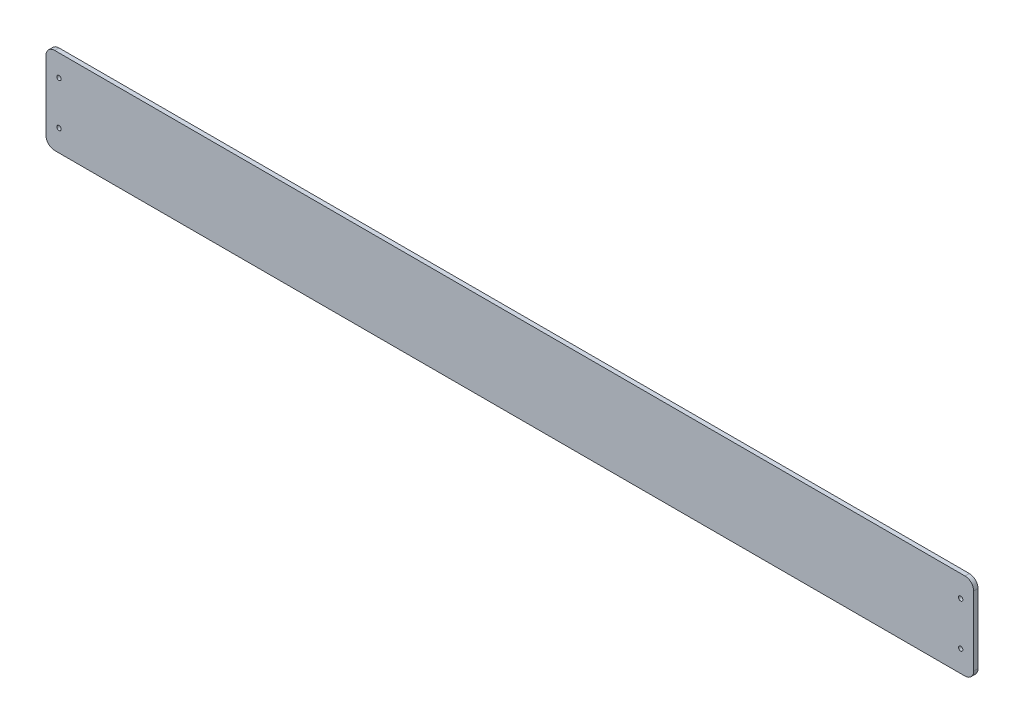
SolidWorks part; units mm, degrees
ref_plane "Alzado" through (0, 0, 0) normal (0, 0, 1) x (1, 0, 0)
ref_plane "Planta" through (0, 0, 0) normal (0, 1, 0) x (1, 0, 0)
ref_plane "Vista lateral" through (0, 0, 0) normal (1, 0, 0) x (0, 0, -1)
sketch "Croquis1" plane through (0, 0, 0) normal (0, 0, 1) x (1, 0, 0)
  line L1 (535, -50) -> (-535, -50)
  line L2 (535, -50) -> (535, 50)
  line L3 (535, 50) -> (-535, 50)
  line L4 (-535, -50) -> (-535, 50)
  line L5 (535, -50) -> (-535, 50) construction
  line L6 (535, 50) -> (-535, -50) construction
  point P0 (0, 0)
  dimension "D1" = 1070
  dimension "D2" = 100
extrude "Extruir1" add sketch "Croquis1" along normal blind 5
fillet "Redondeo1" radius 10 4 edges at (535, -50, 2.5) (535, 50, 2.5) (-535, -50, 2.5) (-535, 50, 2.5)
sketch "Croquis2" plane through (0, 0, 5) normal (0, 0, 1) x (1, 0, 0)
  line L0 (-520, 50) -> (-520, -50) construction
  line L1 (525, 50) -> (-525, 50) construction
  line L2 (-525, -50) -> (525, -50) construction
  line L3 (-535, 40) -> (-535, -40) construction
  line L4 (0, 0) -> (0, 50) construction
  line L5 (0, 0) -> (535, 0) construction
  line L6 (535, -40) -> (535, 40) construction
  circle A0 centre (-520, 25) radius 2.5
  circle A1 centre (-520, -25) radius 2.5
  circle A2 centre (520, -25) radius 2.5
  circle A3 centre (520, 25) radius 2.5
  dimension "D2" = 5
  dimension "D3" = 25
  dimension "D1" = 15
extrude "Extruir2" cut sketch "Croquis2" against normal blind 10
